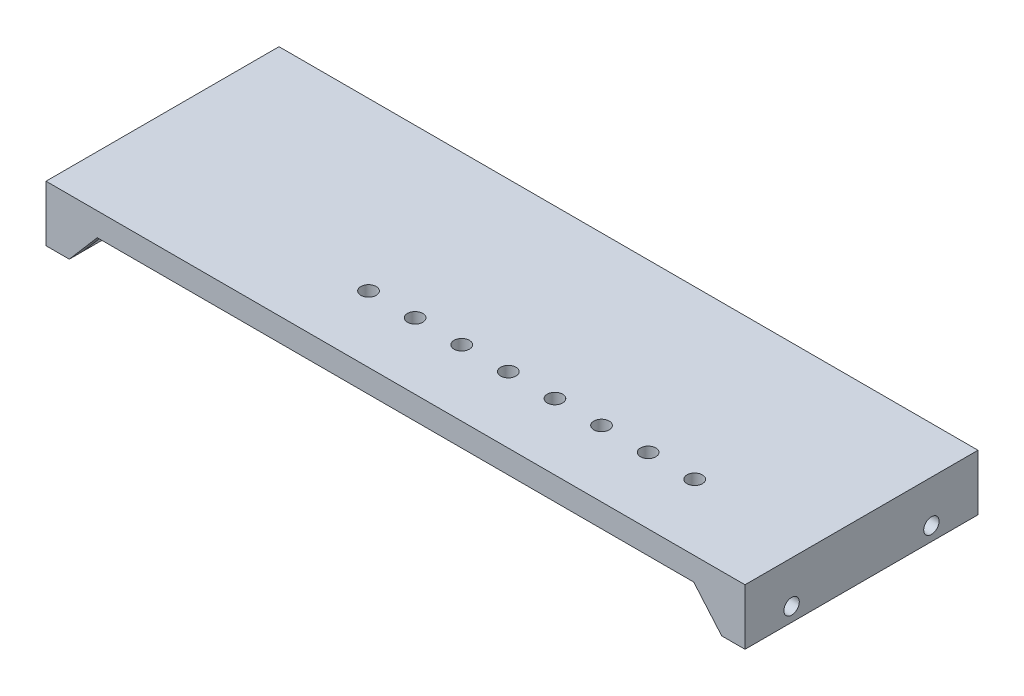
SolidWorks part; units mm, degrees
material "PMMA"
ref_plane "前视基准面" through (0, 0, 0) normal (0, 0, 1) x (1, 0, 0)
ref_plane "上视基准面" through (0, 0, 0) normal (0, 1, 0) x (1, 0, 0)
ref_plane "右视基准面" through (0, 0, 0) normal (1, 0, 0) x (0, 0, -1)
sketch "草图1" plane through (0, 0, 0) normal (0, 0, 1) x (1, 0, 0)
  line L0 (-75, 0) -> (75, 0)
  line L1 (75, 0) -> (75, -12)
  line L2 (75, -12) -> (70, -12)
  line L3 (70, -12) -> (70, -5)
  line L4 (70, -5) -> (-70, -5)
  line L5 (-70, -5) -> (-70, -12)
  line L6 (-70, -12) -> (-75, -12)
  line L7 (-75, -12) -> (-75, 0)
  line L8 (0, -7.4248) -> (0, 9.2484) construction
  dimension "D1" = 5
  dimension "D2" = 5
  dimension "D3" = 150
  dimension "D4" = 12
  dimension "D5" = 12
extrude "凸台-拉伸2" add sketch "草图1" along normal blind 50
sketch "草图3" plane through (-70, 0, 0) normal (1, 0, 0) x (0, 0, -1)
  line L0 (-25, -12) -> (-25, 0) construction
  line L1 (-50, -12) -> (0, -12) construction
  line L3 (-50, -12) -> (0, -12) construction
  line L4 (-50, 0) -> (0, 0) construction
  line L5 (-50, -12) -> (-50, -5) construction
  circle A0 centre (-10, -9) radius 1.65
  circle A1 centre (-40, -9) radius 1.65
  dimension "D2" = 3.3
  dimension "D1" = 3
  dimension "D3" = 10
extrude "切除-拉伸1" cut sketch "草图3" against normal through all both and the other way through all
sketch "草图4" plane through (0, 0, 0) normal (0, 0, -1) x (-1, 0, 0)
  line L0 (64, -5) -> (70, -12)
  line L1 (70, -5) -> (-70, -5) construction
  line L2 (64, -5) -> (70, -5)
  line L4 (70, -5) -> (70, -12)
  dimension "D1" = 6
extrude "凸台-拉伸3" add sketch "草图4" against normal blind 3
sketch "草图5" plane through (0, -5, 0) normal (0, -1, 0) x (1, 0, 0)
  line L0 (70, 25) -> (-70, 25) construction
  line L1 (70, 50) -> (70, 0) construction
  line L2 (-70, 50) -> (-70, 3) construction
ref_plane "基准面3" through (0, 0, 25) normal (0, 0, 1) x (1, 0, 0)
mirror "镜向1" about plane through (0, 0, 25) normal (0, 0, 1) of "凸台-拉伸3"
sketch "草图6" plane through (0, 0, 0) normal (0, 1, 0) x (1, 0, 0)
  line L0 (0, -50) -> (0, 0) construction
  line L1 (75, -50) -> (-75, -50) construction
mirror "镜向2" about plane through (0, 0, 0) normal (1, 0, 0) of "镜向1", "凸台-拉伸3"
sketch "草图7" plane through (0, 0, 0) normal (0, 1, 0) x (1, 0, 0)
  line L0 (75, -50) -> (75, 0) construction
  line L1 (75, -50) -> (-75, -50) construction
  circle A0 centre (50, -35.79) radius 1.65
  circle A1 centre (40, -35.79) radius 1.65
  circle A2 centre (30, -35.79) radius 1.65
  circle A3 centre (20, -35.79) radius 1.65
  circle A4 centre (10, -35.79) radius 1.65
  circle A5 centre (0, -35.79) radius 1.65
  circle A6 centre (-10, -35.79) radius 1.65
  circle A7 centre (-20, -35.79) radius 1.65
  dimension "D1" = 3.3
  dimension "D2" = 25
  dimension "D3" = 14.21
  dimension "D4" = 8
extrude "切除-拉伸2" cut sketch "草图7" against normal blind 10
